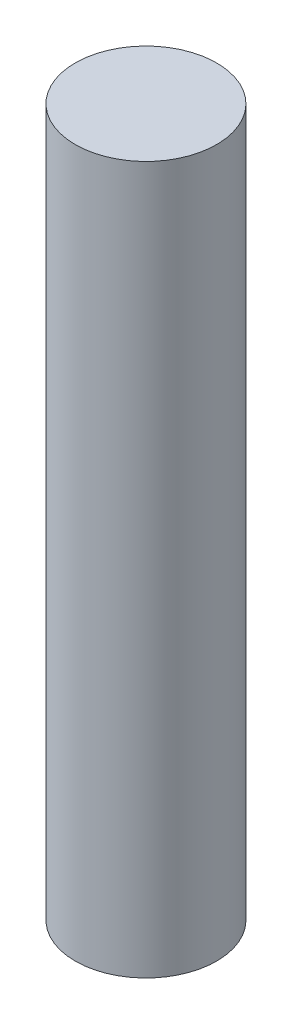
SolidWorks part; units mm, degrees
ref_plane "Plan de face" through (0, 0, 0) normal (0, 0, 1) x (1, 0, 0)
ref_plane "Plan de dessus" through (0, 0, 0) normal (0, 1, 0) x (1, 0, 0)
ref_plane "Plan de droite" through (0, 0, 0) normal (1, 0, 0) x (0, 0, -1)
sketch "Esquisse2" plane through (0, 0, 0) normal (0, 1, 0) x (1, 0, 0)
  circle A0 centre (0, 0) radius 1
extrude "Boss.-Extru.1" add sketch "Esquisse2" along normal blind 10
